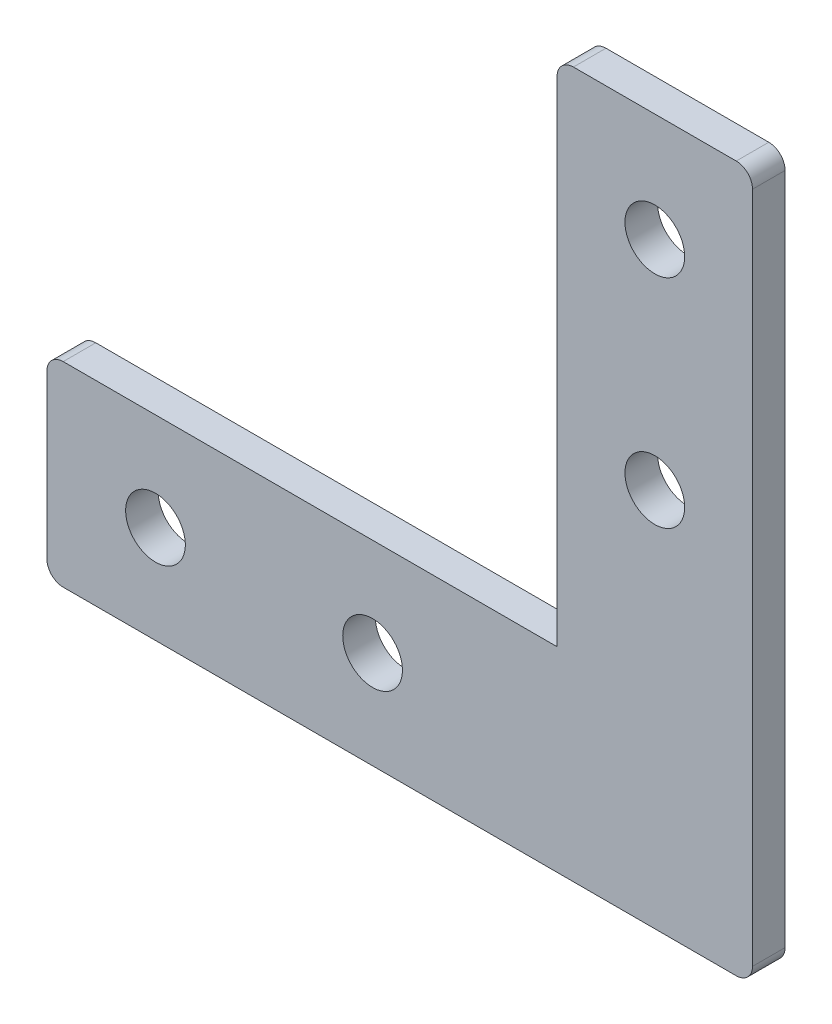
SolidWorks part; units mm, degrees
material "6061 合金"
ref_plane "前视基准面" through (0, 0, 0) normal (0, 0, 1) x (1, 0, 0)
ref_plane "上视基准面" through (0, 0, 0) normal (0, 1, 0) x (1, 0, 0)
ref_plane "右视基准面" through (0, 0, 0) normal (1, 0, 0) x (0, 0, -1)
other "Configuration Table"
sketch "草图1" plane through (0, 0, 0) normal (0, 0, 1) x (1, 0, 0)
  line L0 (0, 16.5) -> (0, 1.5)
  line L1 (1.5, 0) -> (63.5, 0)
  line L2 (65, 1.5) -> (65, 63.5)
  line L3 (63.5, 65) -> (48.5, 65)
  line L4 (47, 63.5) -> (47, 18)
  line L5 (47, 18) -> (1.5, 18)
  circle A0 centre (10, 9) radius 2.75
  circle A1 centre (30, 9) radius 2.75
  circle A2 centre (56, 35) radius 2.75
  circle A3 centre (56, 55) radius 2.75
  arc A4 (1.5, 18) -> (0, 16.5) centre (1.5, 16.5) ccw
  arc A5 (0, 1.5) -> (1.5, 0) centre (1.5, 1.5) ccw
  arc A6 (63.5, 0) -> (65, 1.5) centre (63.5, 1.5) ccw
  arc A7 (65, 63.5) -> (63.5, 65) centre (63.5, 63.5) ccw
  arc A8 (48.5, 65) -> (47, 63.5) centre (48.5, 63.5) ccw
extrude "凸台-拉伸1" add sketch "草图1" against normal blind 3
